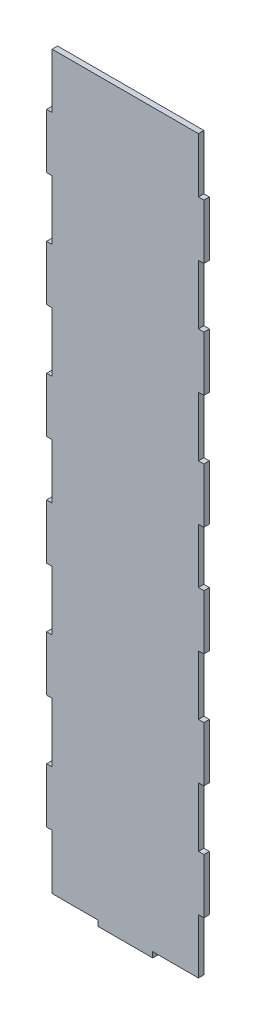
SolidWorks part; units mm, degrees
ref_plane "Plano frontal" through (0, 0, 0) normal (0, 0, 1) x (1, 0, 0)
ref_plane "Plano superior" through (0, 0, 0) normal (0, 1, 0) x (1, 0, 0)
ref_plane "Plano direito" through (0, 0, 0) normal (1, 0, 0) x (0, 0, -1)
sketch "Esboço1" plane through (0, 0, 0) normal (0, 0, 1) x (1, 0, 0)
  line L0 (0, 200) -> (0, -200) construction
  line L1 (-80, -200) -> (-55, -200)
  line L2 (-80, -200) -> (-80, 200)
  line L3 (-80, 200) -> (80, 200)
  line L4 (80, -200) -> (80, 200)
  line L5 (-80, -200) -> (80, 200) construction
  line L6 (-80, 200) -> (80, -200) construction
  line L7 (-80, 0) -> (80, 0) construction
  line L8 (-55, -200) -> (-55, -203)
  line L9 (-55, -203) -> (-25, -203)
  line L10 (-25, -203) -> (-25, -200)
  line L11 (25, -203) -> (25, -200)
  line L12 (55, -203) -> (25, -203)
  line L13 (55, -200) -> (55, -203)
  line L14 (-25, -200) -> (25, -200)
  line L15 (55, -200) -> (80, -200)
  point P0 (0, 0)
  dimension "D1" = 160
  dimension "D2" = 400
  dimension "D3" = 3
  dimension "D4" = 30
  dimension "D5" = 25
extrude "Ressalto-extrusão1" add sketch "Esboço1" along normal blind 3
sketch "Esboço2" plane through (0, 0, 3) normal (0, 0, 1) x (1, 0, 0)
  line L0 (0, 200) -> (0, 170)
  line L1 (80, 200) -> (-80, 200) construction
  line L2 (-25, -200) -> (25, -200) construction
  line L3 (80, 0) -> (-80, 0) construction
  line L4 (80, -200) -> (80, 200) construction
  line L5 (-80, 200) -> (-80, -200) construction
  line L6 (40, -203) -> (40, 200) construction
  line L7 (25, -203) -> (55, -203) construction
  line L8 (0, 170) -> (3, 170)
  line L9 (3, 170) -> (3, 140)
  line L10 (3, 140) -> (0, 140)
  line L11 (0, 107.5) -> (3, 107.5)
  line L12 (3, 107.5) -> (3, 77.5)
  line L13 (3, 77.5) -> (0, 77.5)
  line L14 (0, 45) -> (3, 45)
  line L15 (3, 45) -> (3, 15)
  line L16 (3, 15) -> (0, 15)
  line L17 (3, -140) -> (0, -140)
  line L18 (0, -170) -> (3, -170)
  line L19 (3, -170) -> (3, -140)
  line L20 (3, -77.5) -> (0, -77.5)
  line L21 (3, -107.5) -> (3, -77.5)
  line L22 (0, -107.5) -> (3, -107.5)
  line L23 (3, -15) -> (0, -15)
  line L24 (0, -45) -> (3, -45)
  line L25 (3, -45) -> (3, -15)
  line L26 (0, -170) -> (0, -200)
  line L27 (0, -107.5) -> (0, -140)
  line L28 (0, -45) -> (0, -77.5)
  line L29 (0, 15) -> (0, -15)
  line L30 (0, 77.5) -> (0, 45)
  line L31 (0, 140) -> (0, 107.5)
  line L44 (80, -200) -> (80, 200)
  line L45 (80, 200) -> (-80, 200)
  line L46 (-80, 200) -> (-80, -200)
  line L47 (-80, -200) -> (-55, -200)
  line L48 (-55, -200) -> (-55, -203)
  line L49 (-55, -203) -> (-25, -203)
  line L50 (-25, -203) -> (-25, -200)
  line L51 (-25, -200) -> (25, -200)
  line L52 (25, -200) -> (25, -203)
  line L53 (25, -203) -> (55, -203)
  line L54 (55, -203) -> (55, -200)
  line L55 (55, -200) -> (80, -200)
  line L56 (80, -200) -> (80, 200)
  line L57 (80, 200) -> (0, 200)
  line L63 (0, -200) -> (25, -200)
  line L64 (25, -200) -> (25, -203)
  line L65 (25, -203) -> (55, -203)
  line L66 (55, -203) -> (55, -200)
  line L67 (55, -200) -> (80, -200)
  dimension "D1" = 3
  dimension "D2" = 30
  dimension "D3" = 30
  dimension "D4" = 15
  dimension "D5" = 32.5
  dimension "D6" = 30
  dimension "D7" = 30
  dimension "D8" = 0
extrude "Corte-extrusão3" cut sketch "Esboço2" against normal through all
sketch "Esboço4" plane through (0, 0, 3) normal (0, 0, 1) x (1, 0, 0)
  line L0 (-40, -203) -> (-40, 200) construction
  line L1 (-55, -203) -> (-25, -203) construction
  line L2 (0, 200) -> (-80, 200) construction
  line L3 (0, 0) -> (-80, 0) construction
  line L4 (-80, 200) -> (-80, -200) construction
  line L5 (-80, 170) -> (-83, 170)
  line L6 (-83, 170) -> (-83, 140)
  line L7 (-83, 140) -> (-80, 140)
  line L8 (-80, 140) -> (-80, 170)
  line L9 (-80, 107.5) -> (-83, 107.5)
  line L10 (-83, 107.5) -> (-83, 77.5)
  line L11 (-83, 77.5) -> (-80, 77.5)
  line L12 (-80, 77.5) -> (-80, 107.5)
  line L13 (-80, 45) -> (-83, 45)
  line L14 (-83, 45) -> (-83, 15)
  line L15 (-83, 15) -> (-80, 15)
  line L16 (-80, 15) -> (-80, 45)
  line L17 (-83, -15) -> (-80, -15)
  line L18 (-83, -45) -> (-83, -15)
  line L19 (-80, -45) -> (-83, -45)
  line L20 (-80, -15) -> (-80, -45)
  line L21 (-83, -77.5) -> (-80, -77.5)
  line L22 (-83, -107.5) -> (-83, -77.5)
  line L23 (-80, -107.5) -> (-83, -107.5)
  line L24 (-80, -77.5) -> (-80, -107.5)
  line L25 (-83, -140) -> (-80, -140)
  line L26 (-83, -170) -> (-83, -140)
  line L27 (-80, -170) -> (-83, -170)
  line L28 (-80, -140) -> (-80, -170)
  point P21 (-81.5, 107.5)
  dimension "D1" = 3
  dimension "D2" = 30
  dimension "D3" = 30
  dimension "D4" = 32.5
  dimension "D5" = 32.5
  dimension "D6" = 30
  dimension "D7" = 30
extrude "Ressalto-extrusão3" add sketch "Esboço4" against normal blind 3
